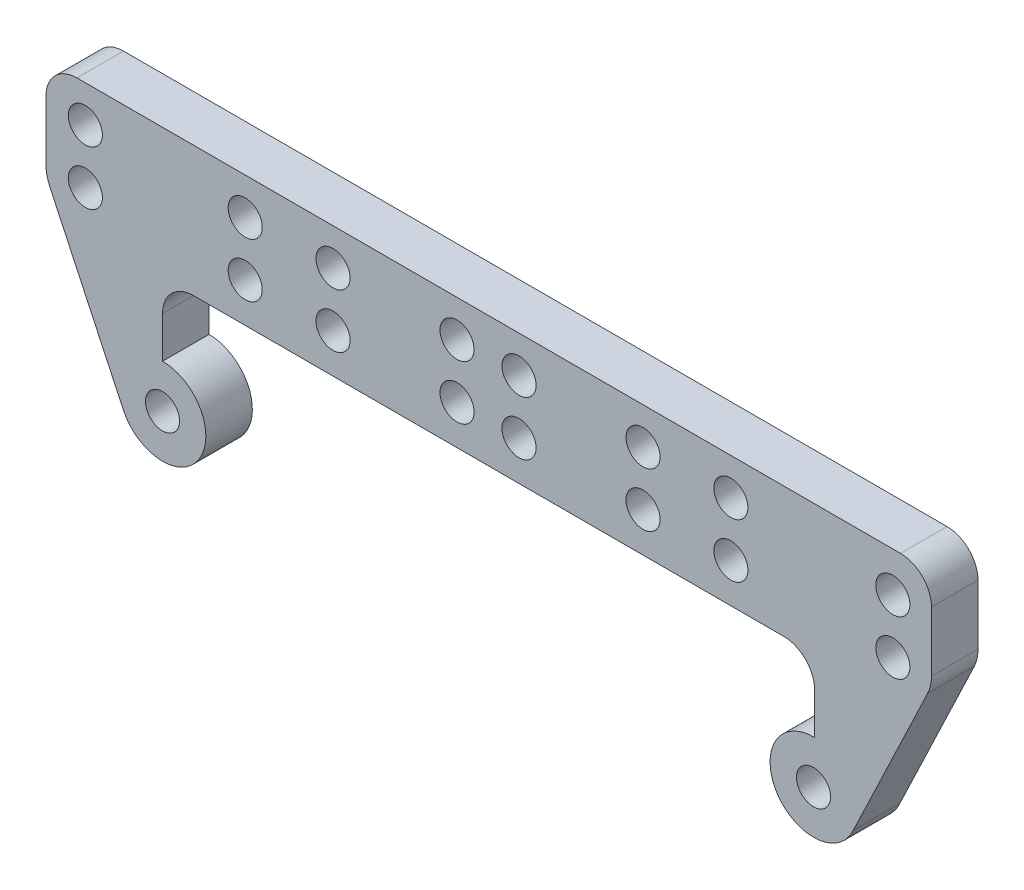
SolidWorks part; units mm, degrees
ref_plane "前视基准面" through (0, 0, 0) normal (0, 0, 1) x (1, 0, 0)
ref_plane "上视基准面" through (0, 0, 0) normal (0, 1, 0) x (1, 0, 0)
ref_plane "右视基准面" through (0, 0, 0) normal (1, 0, 0) x (0, 0, -1)
other "Configuration Table"
sketch "草图1" plane through (0, 0, 0) normal (0, 0, 1) x (1, 0, 0)
  line L0 (8006.879, 5150.9764) -> (8012.079, 5150.9764) construction
  line L3 (7985.9523, 5156.7738) -> (7985.9523, 5150.9764)
  line L5 (8000.229, 5147.1691) -> (8057.3358, 5147.1691)
  line L6 (7993.4343, 5134.1944) -> (7986.3134, 5149.358)
  line L7 (8064.0722, 5134.2663) -> (8071.276, 5149.3578)
  line L8 (8071.6459, 5156.7738) -> (8071.6459, 5150.9915)
  line L9 (7988.9523, 5159.7738) -> (8068.6459, 5159.7738)
  line L10 (7997.229, 5140.1686) -> (7997.229, 5144.1691)
  line L11 (8060.3358, 5140.1814) -> (8060.3358, 5144.1691)
  circle A0 centre (7997.229, 5135.9764) radius 1.65
  arc A6 (8071.276, 5149.3578) -> (8071.6459, 5150.9915) centre (8067.8535, 5150.9915) ccw
  circle A7 centre (8005.229, 5150.9764) radius 1.65
  circle A8 centre (8052.229, 5150.9764) radius 1.65
  circle A9 centre (8013.729, 5150.9764) radius 1.65
  circle A10 centre (8043.729, 5150.9764) radius 1.65
  circle A11 centre (8060.229, 5135.9764) radius 1.65
  circle A12 centre (7989.7596, 5150.9764) radius 1.65
  circle A13 centre (8067.9036, 5150.6806) radius 1.65
  circle A14 centre (8025.729, 5150.9764) radius 1.65
  circle A15 centre (8031.729, 5150.9764) radius 1.65
  arc A16 (7993.4343, 5134.1944) -> (7997.229, 5140.1686) centre (7997.229, 5135.9764) ccw
  arc A17 (8060.3358, 5140.1814) -> (8064.0722, 5134.2663) centre (8060.229, 5135.9764) ccw
  circle A18 centre (8005.229, 5156.2185) radius 1.65
  circle A19 centre (8052.229, 5156.2185) radius 1.65
  circle A20 centre (8013.729, 5156.2185) radius 1.65
  circle A21 centre (8043.729, 5156.2185) radius 1.65
  circle A22 centre (7989.7596, 5156.2185) radius 1.65
  circle A23 centre (8067.9036, 5155.9228) radius 1.65
  circle A24 centre (8025.729, 5156.2185) radius 1.65
  circle A25 centre (8031.729, 5156.2185) radius 1.65
  arc A26 (8071.6459, 5156.7738) -> (8068.6459, 5159.7738) centre (8068.6459, 5156.7738) ccw
  arc A27 (7985.9523, 5156.7738) -> (7988.9523, 5159.7738) centre (7988.9523, 5156.7738) cw
  arc A28 (7985.9523, 5150.9764) -> (7986.3134, 5149.358) centre (7989.7596, 5150.9764) ccw
  arc A29 (8057.3358, 5147.1691) -> (8060.3358, 5144.1691) centre (8057.3358, 5144.1691) cw
  arc A30 (8000.229, 5147.1691) -> (7997.229, 5144.1691) centre (8000.229, 5144.1691) ccw
  point P0 (8028.729, 5135.9764)
  point P12 (8028.729, 5150.9764)
  point P13 (0, 0)
  point P55 (0, 0)
  point P56 (0, 0)
  point P57 (0, 0)
  point P58 (0, 0)
  point P59 (0, 0)
  point P60 (0, 0)
  point P61 (0, 0)
  point P62 (0, 0)
  point P68 (0, 0)
  point P69 (8071.6459, 5147.6912)
  dimension "D2" = 47
  dimension "D6" = 63
  dimension "D8" = 6
  dimension "D10" = 3
  dimension "D11" = 3
  dimension "D1" = 15
  dimension "D3" = 23.5
  dimension "D4" = 30
  dimension "D5" = 15
  dimension "D7" = 31.5
  dimension "D9" = 3
extrude "凸台-拉伸1" add sketch "草图1" along normal blind 4.5
